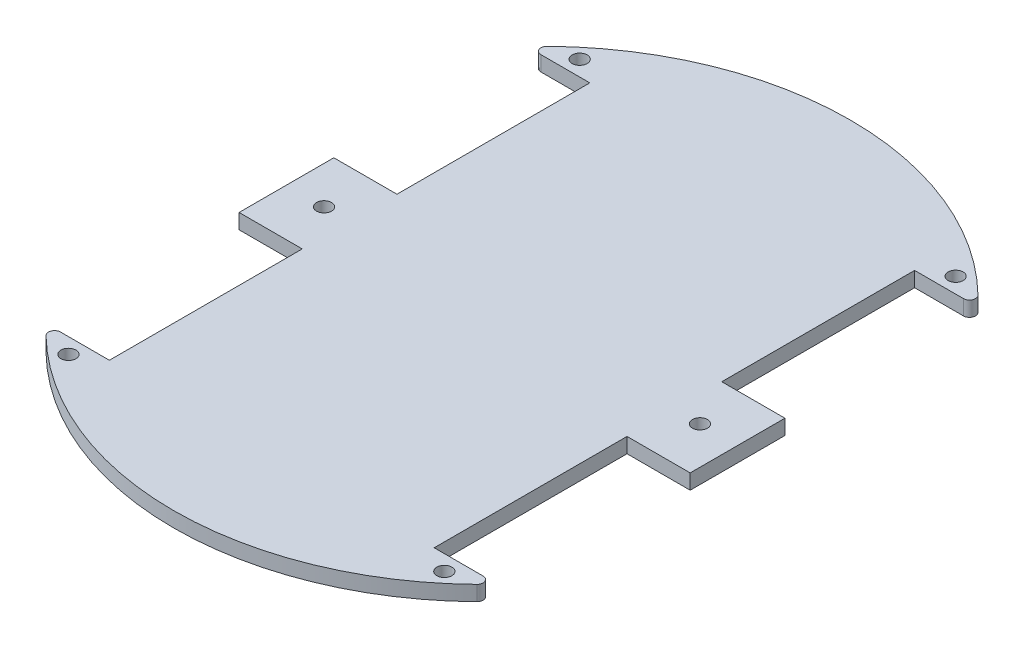
SolidWorks part; units mm, degrees
material "Alumina"
ref_plane "Front Plane" through (0, 0, 0) normal (0, 0, 1) x (1, 0, 0)
ref_plane "Top Plane" through (0, 0, 0) normal (0, 1, 0) x (1, 0, 0)
ref_plane "Right Plane" through (0, 0, 0) normal (1, 0, 0) x (0, 0, -1)
sketch "Sketch1" plane through (0, 0, 0) normal (0, 1, 0) x (1, 0, 0)
  line L0 (126.7418, 27.5057) -> (432.7418, 27.5057) construction
  line L5 (0, 112.5) -> (75, 112.5) construction
  line L6 (-75, 112.5) -> (0, 112.5) construction
  line L7 (-75, 112.5) -> (-75, 79.875) construction
  line L8 (-75, 0) -> (75, 0) construction
  line L9 (75, 112.5) -> (75, 79.875) construction
  line L10 (-75, 112.5) -> (75, 0) construction
  line L11 (-75, 0) -> (75, 112.5) construction
  line L12 (-75, 15.75) -> (-75, -15.75)
  line L13 (75, 15.75) -> (75, 0)
  line L14 (-75, 0) -> (75, 0) construction
  line L15 (0, -56.25) -> (0, 56.25) construction
  line L16 (54, 79.875) -> (54, 15.75)
  line L17 (54, 15.75) -> (75, 15.75)
  line L18 (-75, 0) -> (75, -112.5) construction
  line L19 (-75, -112.5) -> (75, 0) construction
  line L20 (75, -112.5) -> (75, -79.875) construction
  line L21 (-75, -112.5) -> (-75, -79.875) construction
  line L22 (-75, -112.5) -> (0, -112.5) construction
  line L23 (0, -112.5) -> (75, -112.5) construction
  line L24 (-54, -79.875) -> (-70.252, -79.875)
  line L25 (54, 79.875) -> (70.252, 79.875)
  line L26 (-75, 15.75) -> (-75, -15.75)
  line L27 (-54, 15.75) -> (-75, 15.75)
  line L28 (-54, 79.875) -> (-54, 15.75)
  line L29 (-54, 79.875) -> (-70.252, 79.875)
  line L30 (-54, -79.875) -> (-54, -15.75)
  line L31 (-54, -15.75) -> (-75, -15.75)
  line L32 (54, -79.875) -> (70.252, -79.875)
  line L33 (54, -15.75) -> (75, -15.75)
  line L34 (54, -79.875) -> (54, -15.75)
  line L35 (75, -15.75) -> (75, 0)
  arc A1 (71.6498, 83.3055) -> (-71.6498, 83.3055) centre (0, 9.9806) ccw
  arc A2 (71.6498, -83.3055) -> (-71.6498, -83.3055) centre (0, -9.9806) cw
  arc A3 (-70.252, -79.875) -> (-71.6498, -83.3055) centre (-70.252, -81.875) ccw
  arc A4 (70.252, -79.875) -> (71.6498, -83.3055) centre (70.252, -81.875) cw
  arc A5 (71.6498, 83.3055) -> (70.252, 79.875) centre (70.252, 81.875) cw
  arc A6 (-71.6498, 83.3055) -> (-70.252, 79.875) centre (-70.252, 81.875) ccw
  point P0 (0, 56.25)
  point P16 (0, 0)
  point P18 (0, 0)
  point P35 (0, -56.25)
  dimension "D3" = 64.125
  dimension "D5" = 2
  dimension "D1" = 112.5
  dimension "D2" = 150
  dimension "D4" = 15.75
extrude "Boss-Extrude1" add sketch "Sketch1" along normal blind 5 contours A2 L32 L34 L33 L35 L13 L17 L16 L25 A1 L29 L28 L27 L12 L31 L30 L24
sketch "Sketch2" plane through (0, 5, 0) normal (0, 1, 0) x (1, 0, 0)
  line L1 (-62.5, -85) -> (62.5, -85) construction
  line L2 (-62.5, -85) -> (-62.5, 85) construction
  line L3 (-62.5, 85) -> (62.5, 85) construction
  line L4 (62.5, -85) -> (62.5, 85) construction
  line L5 (-62.5, -85) -> (62.5, 85) construction
  line L6 (-62.5, 85) -> (62.5, -85) construction
  circle A0 centre (-62.5, 85) radius 2.5
  circle A1 centre (62.5, 85) radius 2.5
  circle A2 centre (62.5, 0) radius 2.5
  circle A3 centre (62.5, -85) radius 2.5
  circle A4 centre (-62.5, 0) radius 2.5
  circle A5 centre (-62.5, -85) radius 2.5
  point P0 (0, 0)
  dimension "D3" = 5
  dimension "D1" = 125
  dimension "D2" = 170
  dimension "D4" = 2
  dimension "D5" = 3
extrude "Cut-Extrude1" cut sketch "Sketch2" against normal through all
